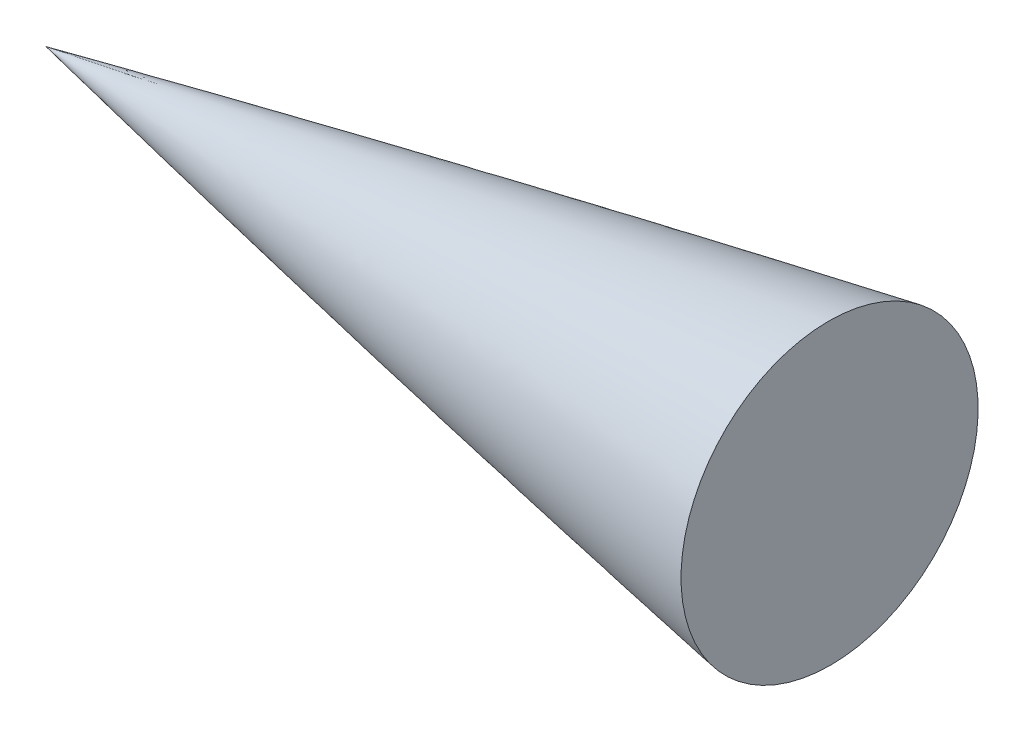
SolidWorks part; units mm, degrees
material "1060 Alloy"
ref_plane "Front" through (0, 0, 0) normal (0, 0, 1) x (1, 0, 0)
ref_plane "Top" through (0, 0, 0) normal (0, 1, 0) x (1, 0, 0)
ref_plane "Right" through (0, 0, 0) normal (1, 0, 0) x (0, 0, -1)
sketch "Sketch1" plane through (0, 0, 0) normal (0, 0, 1) x (1, 0, 0)
  line L0 (0, 0) -> (100, 0.6429)
  line L1 (100, 0.6429) -> (100, 19.6229)
  spline S0 degree 4 poles (-9.9642, -2.1151) (-9.2552, -1.9638) (-7.8851, -1.6717) (-6.0153, -1.2721) (-0.9836, -0.2068) (1.2407, 0.2622) (7.7707, 1.6322) (11.4879, 2.4026) (16.861, 3.5156) (21.2403, 4.4123) (26.2216, 5.4294) (30.8418, 6.3637) (35.6804, 7.3376) (40.3929, 8.278) (45.1768, 9.2272) (49.931, 10.163) (54.6863, 11.0932) (59.4742, 12.0223) (64.1927, 12.9325) (69.0403, 13.8594) (73.6713, 14.7405) (78.6671, 15.6812) (83.0612, 16.506) (88.4553, 17.5059) (92.1898, 18.1977) (98.7577, 19.3978) (100.9965, 19.8045) (106.0791, 20.7237) (107.961, 21.0602) (109.3487, 21.3091) (110.066, 21.4376) knots 0 0 0 0 0 0.020833 0.041665 0.082825 0.12254 0.162255 0.201971 0.241686 0.281401 0.321116 0.360831 0.400546 0.440261 0.479976 0.519691 0.559407 0.599122 0.638837 0.678552 0.718267 0.757982 0.797697 0.837412 0.877127 0.916843 0.958171 0.979085 1 1 1 1 1 construction
  spline S1 degree 4 poles (0, 0) (0.9901, 0.2087) (2.9173, 0.6139) (7.7707, 1.6322) (11.4879, 2.4026) (16.861, 3.5156) (21.2403, 4.4123) (26.2216, 5.4294) (30.8418, 6.3637) (35.6804, 7.3376) (40.3929, 8.278) (45.1768, 9.2272) (49.931, 10.163) (54.6863, 11.0932) (59.4742, 12.0223) (64.1927, 12.9325) (69.0403, 13.8594) (73.6713, 14.7405) (78.6671, 15.6812) (83.0612, 16.506) (88.4553, 17.5059) (92.1898, 18.1977) (97.0662, 19.0887) (99.0045, 19.442) (100, 19.6229) knots 0.082825 0.082825 0.082825 0.082825 0.082825 0.12254 0.162255 0.201971 0.241686 0.281401 0.321116 0.360831 0.400546 0.440261 0.479976 0.519691 0.559407 0.599122 0.638837 0.678552 0.718267 0.757982 0.797697 0.837412 0.877127 0.916843 0.916843 0.916843 0.916843 0.916843
  dimension "D1" = 100
  dimension "D2" = 18.98
revolve "Revolve1" add sketch "Sketch1" angle 360 about L0
